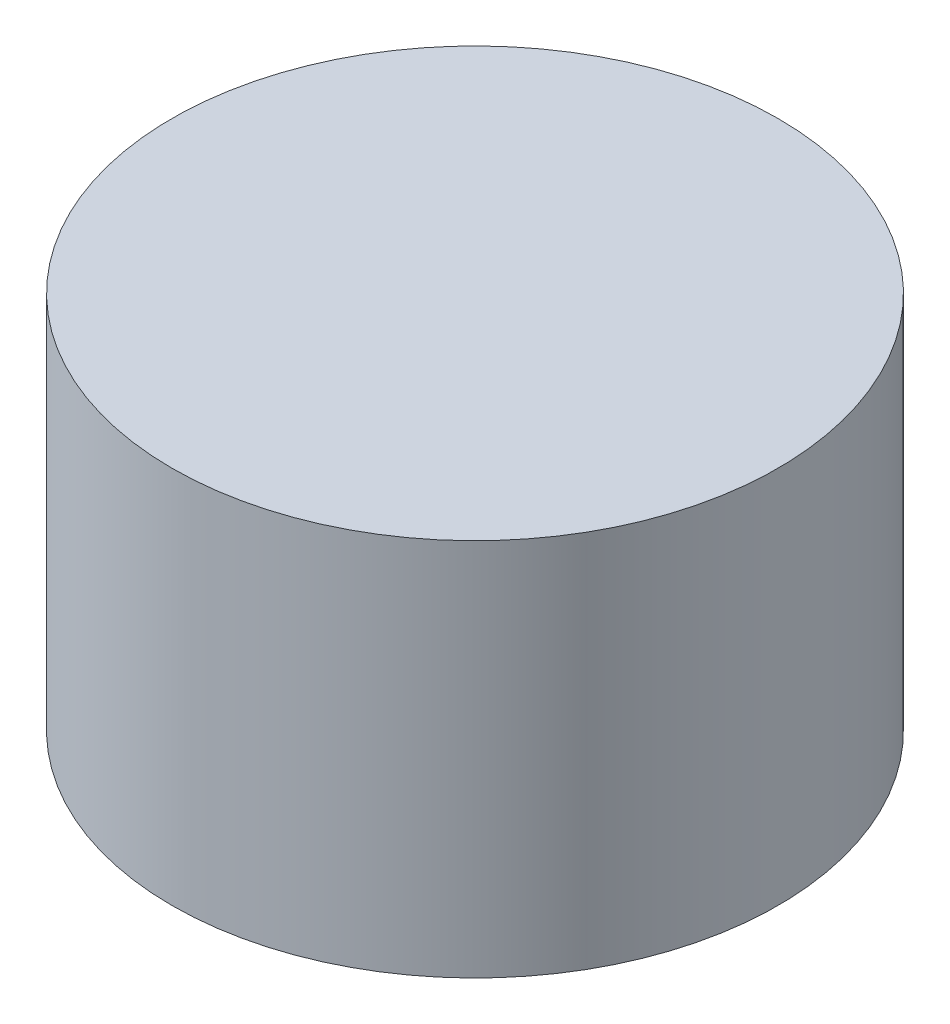
SolidWorks part; units mm, degrees
material "PVC 0.007 Plasticized"
ref_plane "Front Plane" through (0, 0, 0) normal (0, 0, 1) x (1, 0, 0)
ref_plane "Top Plane" through (0, 0, 0) normal (0, 1, 0) x (1, 0, 0)
ref_plane "Right Plane" through (0, 0, 0) normal (1, 0, 0) x (0, 0, -1)
sketch "Sketch1" plane through (0, 0, 0) normal (0, 1, 0) x (1, 0, 0)
  circle A0 centre (0, 0) radius 20.32
  point P3 (0, 0)
  dimension "D1" = 40.64
extrude "Boss-Extrude1" add sketch "Sketch1" along normal blind 25.4
sketch "Sketch2" plane through (0, 0, 0) normal (0, -1, 0) x (1, 0, 0)
  circle A0 centre (0, 0) radius 16.51
extrude "Cut-Extrude1" cut sketch "Sketch2" against normal blind 15.24
